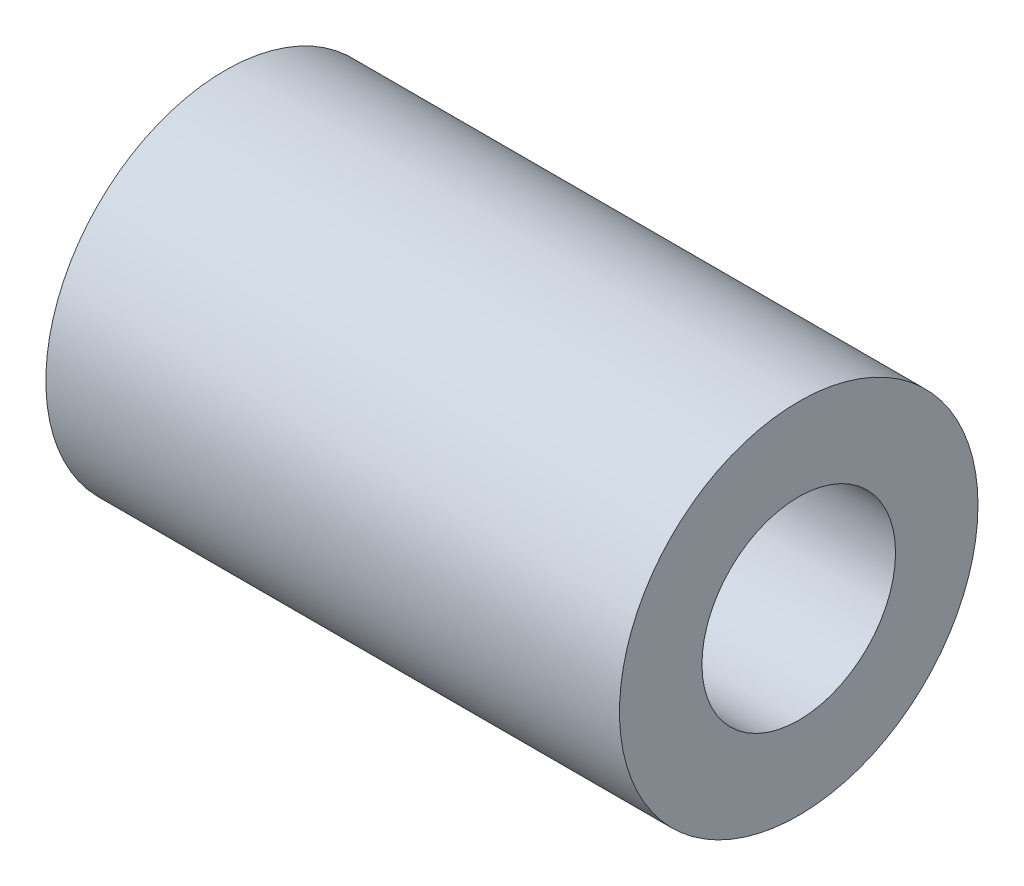
SolidWorks part; units mm, degrees
ref_plane "Спереди" through (0, 0, 0) normal (0, 0, 1) x (1, 0, 0)
ref_plane "Сверху" through (0, 0, 0) normal (0, 1, 0) x (1, 0, 0)
ref_plane "Справа" through (0, 0, 0) normal (1, 0, 0) x (0, 0, -1)
sketch "Эскиз1" plane through (0, 0, 0) normal (1, 0, 0) x (0, 0, -1)
  circle A0 centre (0, 0) radius 7.5
  circle A1 centre (0, 0) radius 4.05
  dimension "D1" = 15
  dimension "D2" = 8.1
extrude "Бобышка-Вытянуть1" add sketch "Эскиз1" along normal blind 24
